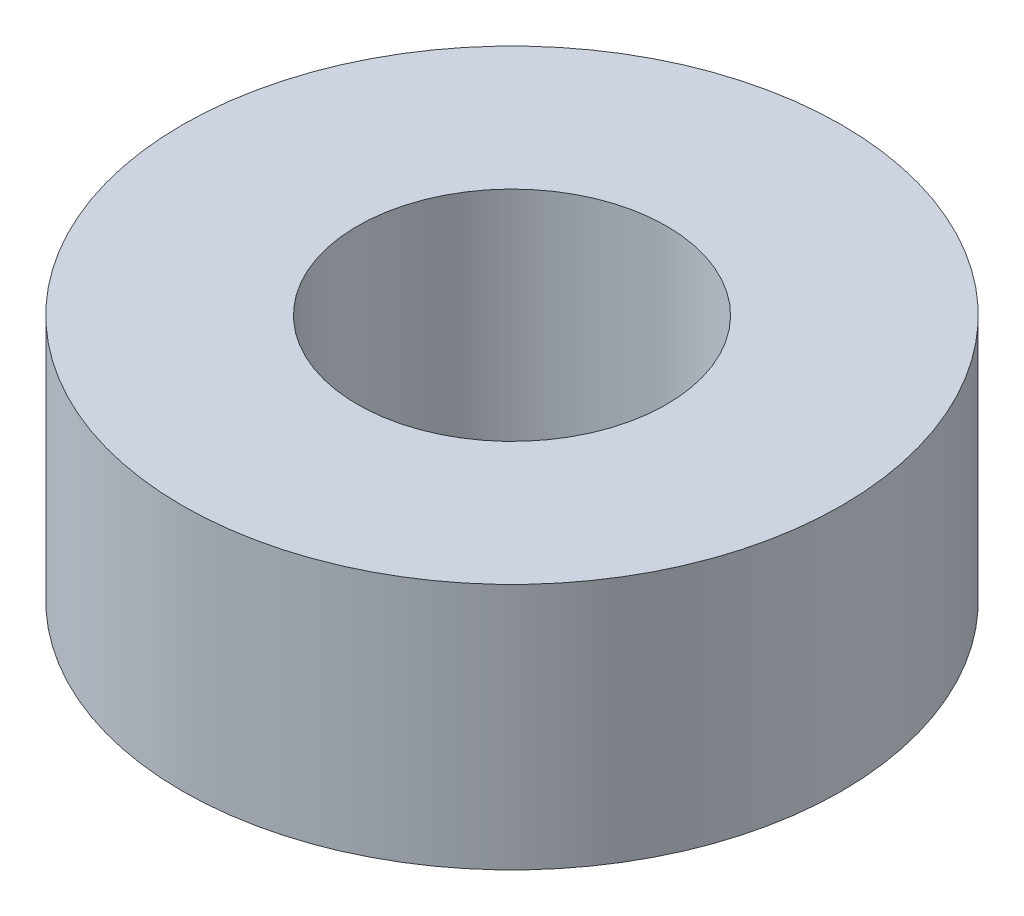
SolidWorks part; units mm, degrees
ref_plane "Front Plane" through (0, 0, 0) normal (0, 0, 1) x (1, 0, 0)
ref_plane "Top Plane" through (0, 0, 0) normal (0, 1, 0) x (1, 0, 0)
ref_plane "Right Plane" through (0, 0, 0) normal (1, 0, 0) x (0, 0, -1)
sketch "Sketch2" plane through (0, 0, 0) normal (0, 1, 0) x (1, 0, 0)
  circle A0 centre (0, 0) radius 20.32
  circle A1 centre (0, 0) radius 9.525
  dimension "D1" = 19.05
  dimension "D2" = 40.64
extrude "Boss-Extrude1" add sketch "Sketch2" along normal blind 15.24
